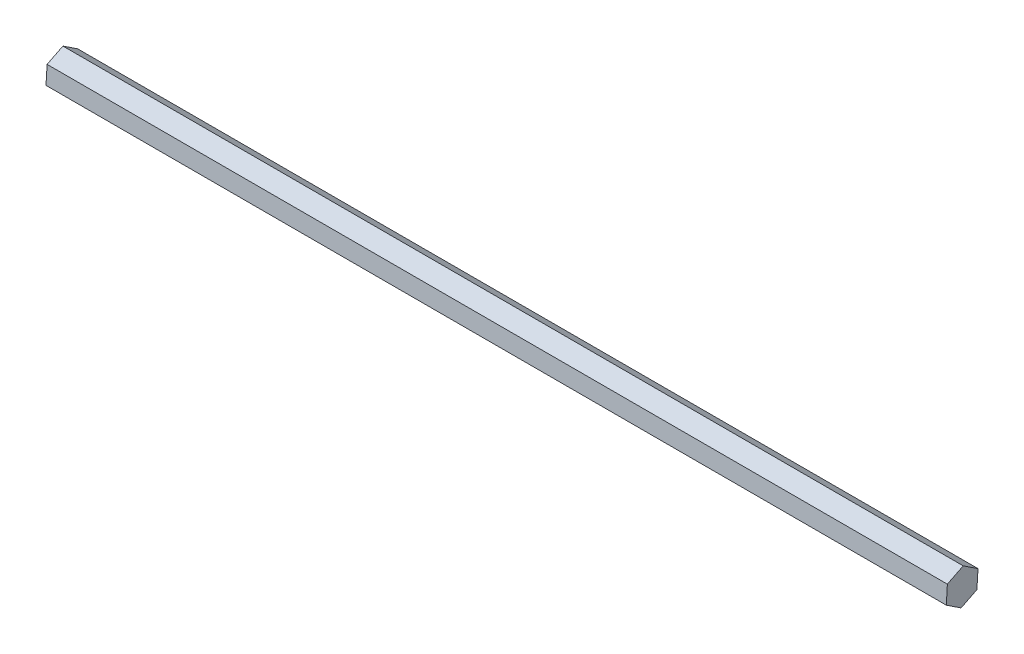
SolidWorks part; units mm, degrees
ref_plane "Front Plane" through (0, 0, 0) normal (0, 0, 1) x (1, 0, 0)
ref_plane "Top Plane" through (0, 0, 0) normal (0, 1, 0) x (1, 0, 0)
ref_plane "Right Plane" through (0, 0, 0) normal (1, 0, 0) x (0, 0, -1)
sketch "Sketch1" plane through (0, 0, 0) normal (1, 0, 0) x (0, 0, -1)
  line L1 (6.2514, -4.1372) -> (6.7086, 3.3452)
  line L2 (6.7086, 3.3452) -> (0.4573, 7.4825)
  line L3 (0.4573, 7.4825) -> (-6.2514, 4.1372)
  line L4 (-6.2514, 4.1372) -> (-6.7086, -3.3452)
  line L5 (-6.7086, -3.3452) -> (-0.4573, -7.4825)
  line L6 (-0.4573, -7.4825) -> (6.2514, -4.1372)
  circle A0 centre (0, 0) radius 6.4921 construction
extrude "Boss-Extrude2" add sketch "Sketch1" along normal blind 381 contours L1 L2 L3 L4 L5 L6
